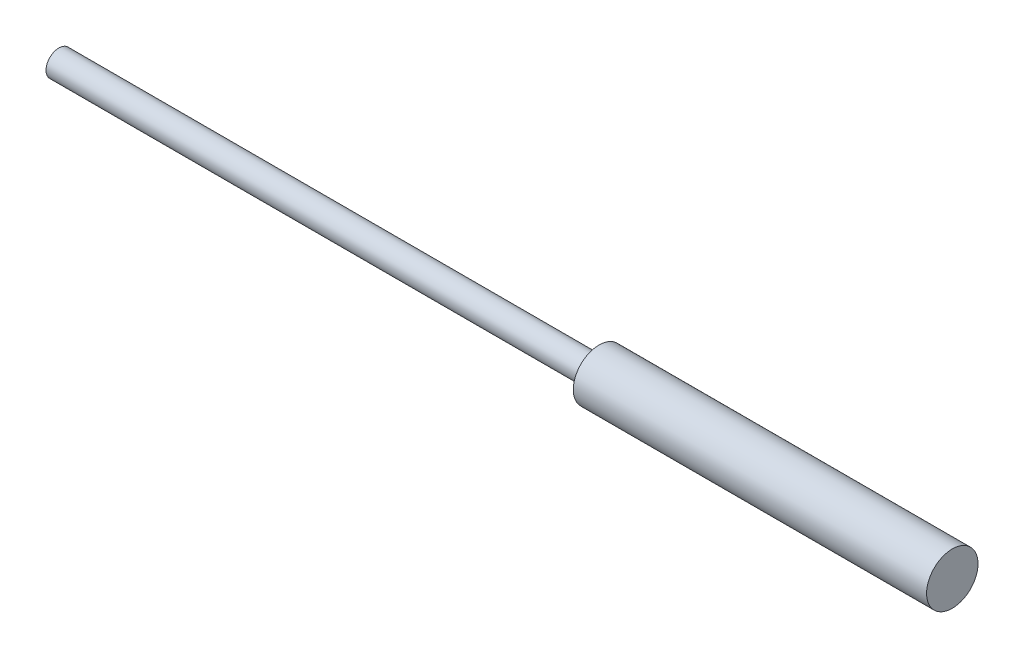
SolidWorks part; units mm, degrees
ref_plane "Front" through (0, 0, 0) normal (0, 0, 1) x (1, 0, 0)
ref_plane "Top" through (0, 0, 0) normal (0, 1, 0) x (1, 0, 0)
ref_plane "Right" through (0, 0, 0) normal (1, 0, 0) x (0, 0, -1)
sketch "Sketch3" plane through (2551.3496, 0, 0) normal (-1, 0, 0) x (0, 0, 1)
  circle A0 centre (18.5, 11.5) radius 1.5 construction
  circle A1 centre (18.5, 11.5) radius 1.5
extrude "Base-Extrude" add sketch "Sketch3" against normal up to surface (104.2 mm away)
sketch "Sketch4" plane through (2655.5496, 0, 0) normal (-1, 0, 0) x (0, 0, 1)
  circle A1 centre (18.5, 11.5) radius 3 construction
  circle A2 centre (18.5, 11.5) radius 3
extrude "Boss-Extrude1" add sketch "Sketch4" along normal up to surface (41.2 mm away)
